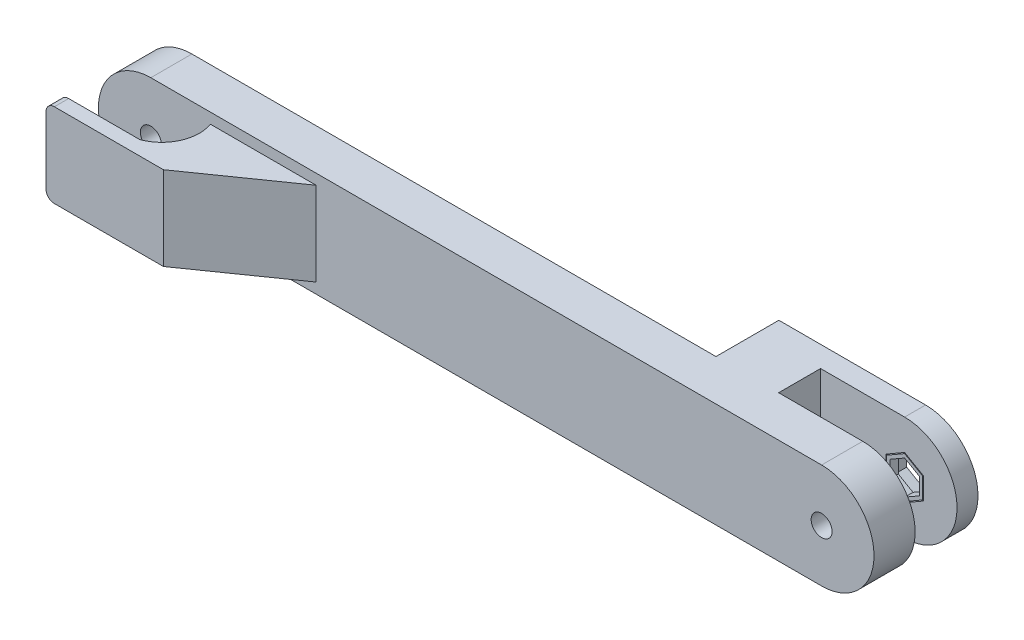
SolidWorks part; units mm, degrees
ref_plane "Front" through (0, 0, 0) normal (0, 0, 1) x (1, 0, 0)
ref_plane "Top" through (0, 0, 0) normal (0, 1, 0) x (1, 0, 0)
ref_plane "Right" through (0, 0, 0) normal (1, 0, 0) x (0, 0, -1)
sketch "Sketch1" plane through (0, 0, 0) normal (0, 0, 1) x (1, 0, 0)
  line L0 (299.8703, -79.0606) -> (503.0703, -79.0606) construction
  line L1 (299.8703, -63.1856) -> (503.0703, -63.1856)
  line L2 (299.8703, -94.9356) -> (503.0703, -94.9356)
  line L3 (401.4703, -94.9356) -> (401.4703, -63.1856) construction
  arc A0 (299.8703, -63.1856) -> (299.8703, -94.9356) centre (299.8703, -79.0606) ccw
  arc A1 (503.0703, -94.9356) -> (503.0703, -63.1856) centre (503.0703, -79.0606) ccw
  circle A2 centre (299.8703, -79.0606) radius 3.175
  circle A3 centre (503.0703, -79.0606) radius 3.175
  point P2 (401.4703, -79.0606)
  dimension "D1" = 203.2
  dimension "D2" = 15.875
  dimension "D3" = 31.75
extrude "Boss-Extrude1" add sketch "Sketch1" along normal blind 12.446
sketch "Sketch2" plane through (0, 0, 0) normal (0, 0, -1) x (-1, 0, 0)
  line L5 (-477.6703, -66.3606) -> (-477.6703, -91.7606)
  line L6 (-513.2303, -91.7606) -> (-477.6703, -91.7606)
  line L7 (-515.7703, -89.2206) -> (-515.7703, -68.9006)
  line L8 (-513.2303, -66.3606) -> (-477.6703, -66.3606)
  line L10 (-515.7703, -91.7606) -> (-490.3703, -66.3606) construction
  line L11 (-515.7703, -66.3606) -> (-490.3703, -91.7606) construction
  arc A0 (-513.2303, -91.7606) -> (-515.7703, -89.2206) centre (-513.2303, -89.2206) cw
  arc A3 (-515.7703, -68.9006) -> (-513.2303, -66.3606) centre (-513.2303, -68.9006) cw
  point P0 (-503.0703, -79.0606)
  dimension "D3" = 2.54
  dimension "D1" = 25.4
  dimension "D2" = 25.4
  dimension "D4" = 35.56
ref_plane "Plane5" through (401.447, 0, 0) normal (1, 0, 0) x (0, 0, -1)
surface "Surface-MidSurface2" parameters "D0"=50000
sketch "Sketch7" plane through (0, 0, 12.446) normal (0, 0, 1) x (1, 0, 0)
  line L0 (310.0303, -66.3606) -> (312.5703, -66.3606)
  line L1 (289.7103, -91.7606) -> (310.0303, -91.7606)
  line L2 (287.1703, -89.2206) -> (287.1703, -68.9006)
  line L3 (289.7103, -66.3606) -> (310.0303, -66.3606)
  line L5 (287.1703, -91.7606) -> (312.5703, -66.3606) construction
  line L6 (287.1703, -66.3606) -> (312.5703, -91.7606) construction
  line L7 (312.5703, -66.3606) -> (322.7303, -66.3606)
  line L8 (322.7303, -66.3606) -> (322.7303, -91.7606)
  line L9 (310.0303, -91.7606) -> (322.7303, -91.7606)
  arc A0 (289.7103, -91.7606) -> (287.1703, -89.2206) centre (289.7103, -89.2206) cw
  arc A3 (287.1703, -68.9006) -> (289.7103, -66.3606) centre (289.7103, -68.9006) cw
  point P0 (299.8703, -79.0606)
  dimension "D3" = 2.54
  dimension "D1" = 25.4
  dimension "D2" = 25.4
  dimension "D4" = 10.16
extrude "Boss-Extrude8" add sketch "Sketch7" along normal blind 19.05
sketch "Sketch8" plane through (0, -66.3606, 0) normal (0, 1, 0) x (1, 0, 0)
  line L0 (287.1703, -12.446) -> (317.9043, -12.446)
  line L1 (503.0703, -12.446) -> (299.8703, -12.446) construction
  line L2 (287.1703, -12.446) -> (287.1703, -27.178)
  line L3 (287.1703, -31.496) -> (287.1703, -12.446) construction
  line L4 (287.1703, -27.178) -> (311.3003, -27.178)
  arc A0 (317.9043, -12.446) -> (311.3003, -27.178) centre (307.218, -16.5018) cw
  dimension "D1" = 30.734
  dimension "D2" = 14.732
  dimension "D3" = 24.13
extrude "Cut-Extrude3" cut sketch "Sketch8" against normal blind 41.148
sketch "Sketch9" plane through (0, -66.3606, 0) normal (0, 1, 0) x (1, 0, 0)
  line L0 (322.7303, -31.496) -> (349.9365, -12.446)
  line L1 (503.0703, -12.446) -> (299.8703, -12.446) construction
  line L4 (322.7303, -12.446) -> (349.9365, -12.446)
  line L5 (322.7303, -31.496) -> (322.7303, -12.446)
  dimension "D1" = 35
extrude "Boss-Extrude9" add sketch "Sketch9" against normal blind 25.4
sketch "Sketch10" plane through (0, 0, 0) normal (0, 0, -1) x (-1, 0, 0)
  line L0 (-503.0703, -94.9356) -> (-458.6203, -94.9356)
  line L1 (-503.0703, -72.4615) -> (-508.7853, -75.7611)
  line L2 (-508.7853, -75.7611) -> (-508.7853, -82.3602)
  line L3 (-508.7853, -82.3602) -> (-503.0703, -85.6597)
  line L4 (-503.0703, -85.6597) -> (-497.3553, -82.3602)
  line L5 (-497.3553, -82.3602) -> (-497.3553, -75.7611)
  line L6 (-497.3553, -75.7611) -> (-503.0703, -72.4615)
  line L7 (-299.8703, -94.9356) -> (-503.0703, -94.9356) construction
  line L8 (-458.6203, -94.9356) -> (-458.6203, -63.1856)
  line L9 (-503.0703, -63.1856) -> (-299.8703, -63.1856) construction
  line L10 (-458.6203, -63.1856) -> (-503.0703, -63.1856)
  arc A0 (-503.0703, -63.1856) -> (-503.0703, -94.9356) centre (-503.0703, -79.0606) ccw
  circle A1 centre (-503.0703, -79.0606) radius 5.715 construction
  dimension "D1" = 44.45
  dimension "D2" = 11.43
extrude "Boss-Extrude10" add sketch "Sketch10" along normal blind 19.05
sketch "Sketch11" plane through (0, -63.1856, 0) normal (0, 1, 0) x (1, 0, 0)
  line L0 (518.9453, 0) -> (477.6068, 0)
  line L1 (518.9453, -12.446) -> (518.9453, 19.05) construction
  line L2 (518.9453, 12.7) -> (518.9453, 0)
  line L5 (518.9453, 12.7) -> (477.6068, 12.7)
  line L7 (477.6068, 12.7) -> (477.6068, 0)
extrude "Cut-Extrude4" cut sketch "Sketch11" against normal blind 35.56
ref_plane "Plane6" through (0, 0, -12.7) normal (0, 0, -1) x (-1, 0, 0)
sketch "Sketch13" plane through (0, 0, -12.7) normal (0, 0, -1) x (-1, 0, 0)
  line L1 (-503.0703, -72.7768) -> (-508.5122, -75.9187)
  line L2 (-508.5122, -75.9187) -> (-508.5122, -82.2025)
  line L3 (-508.5122, -82.2025) -> (-503.0703, -85.3444)
  line L4 (-503.0703, -85.3444) -> (-497.6283, -82.2025)
  line L5 (-497.6283, -82.2025) -> (-497.6283, -75.9187)
  line L6 (-497.6283, -75.9187) -> (-503.0703, -72.7768)
  line L7 (-503.0703, -73.9241) -> (-507.5186, -76.4924)
  line L8 (-507.5186, -76.4924) -> (-507.5186, -81.6289)
  line L9 (-507.5186, -81.6289) -> (-503.0703, -84.1971)
  line L10 (-503.0703, -84.1971) -> (-498.6219, -81.6289)
  line L11 (-498.6219, -81.6289) -> (-498.6219, -76.4924)
  line L12 (-498.6219, -76.4924) -> (-503.0703, -73.9241)
  circle A0 centre (-503.0703, -79.0606) radius 5.442 construction
  circle A1 centre (-503.0703, -79.0606) radius 4.4483 construction
extrude "Boss-Extrude11" add sketch "Sketch13" along normal blind 2.54
